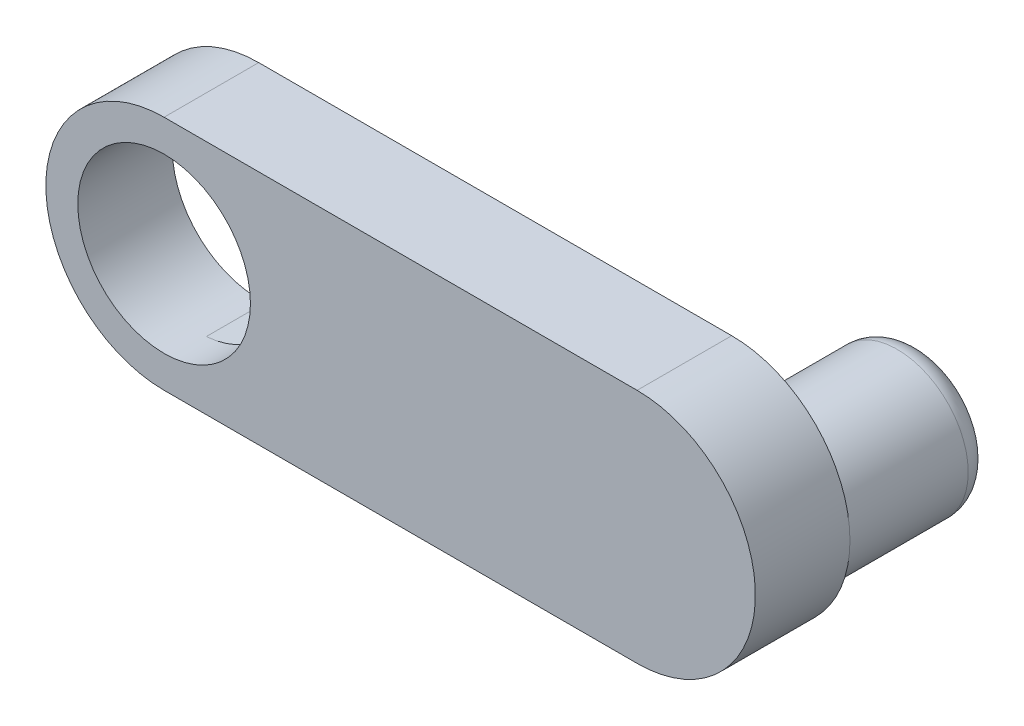
SolidWorks part; units mm, degrees
ref_plane "前视基准面" through (0, 0, 0) normal (0, 0, 1) x (1, 0, 0)
ref_plane "上视基准面" through (0, 0, 0) normal (0, 1, 0) x (1, 0, 0)
ref_plane "右视基准面" through (0, 0, 0) normal (1, 0, 0) x (0, 0, -1)
other "Configuration Table"
sketch "草图1" plane through (0, 0, 0) normal (0, 0, 1) x (1, 0, 0)
  line L3 (0, 5) -> (20, 5)
  line L4 (0, -5) -> (20, -5)
  arc A2 (0, 5) -> (0, -5) centre (0, 0) ccw
  arc A4 (20, -5) -> (20, 5) centre (20, 0) ccw
  dimension "D4" = 10
  dimension "D5" = 20
extrude "凸台-拉伸3" add sketch "草图1" along normal blind 4 contours L3 A4 L4 A2
sketch "草图4" plane through (0, 0, 0) normal (0, 0, 1) x (1, 0, 0)
  circle A0 centre (22, 0) radius 3
  arc A1 (20, -5) -> (20, 5) centre (20, 0) ccw construction
  dimension "D1" = 6
extrude "凸台-拉伸4" add sketch "草图4" against normal blind 6 contours A0
sketch "草图6" plane through (0, 0, 0) normal (0, 0, -1) x (-1, 0, 0)
  line L0 (-16.1875, 2.3927) -> (-0.2852, 3.6388)
  line L1 (-16.1875, -2.3927) -> (-0.2852, -3.6388)
  arc A0 (-0.2852, -3.6388) -> (-0.2852, 3.6388) centre (0, 0) ccw
  arc A1 (-16.1875, 2.3927) -> (-16.1875, -2.3927) centre (-16, 0) ccw
  dimension "D1" = 7.3
  dimension "D2" = 4.8
  dimension "D3" = 16
extrude "切除-拉伸1" cut sketch "草图6" against normal blind 2.5 contours L0 A0 L1 A1
sketch "草图7" plane through (0, 0, 2.5) normal (0, 0, -1) x (-1, 0, 0)
  circle A0 centre (0, 0) radius 3.65
  arc A1 (-0.2852, -3.6388) -> (-0.2852, 3.6388) centre (0, 0) ccw construction
extrude "切除-拉伸2" cut sketch "草图7" against normal through all
fillet "圆角1" radius 1 1 edges at (25, 0, -6)
